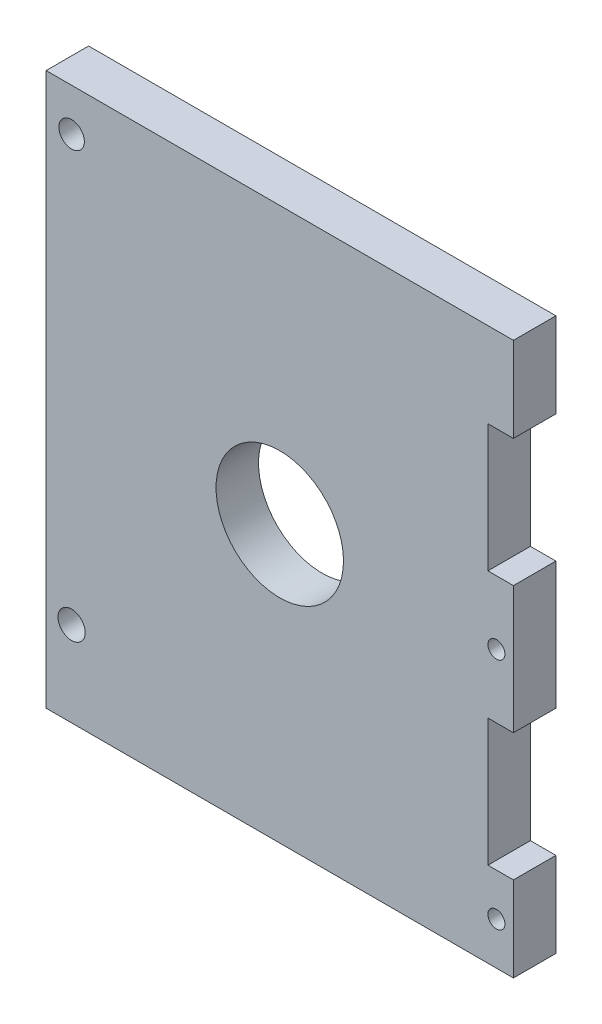
SolidWorks part; units mm, degrees
ref_plane "Front" through (0, 0, 0) normal (0, 0, 1) x (1, 0, 0)
ref_plane "Top" through (0, 0, 0) normal (0, 1, 0) x (1, 0, 0)
ref_plane "Right" through (0, 0, 0) normal (1, 0, 0) x (0, 0, -1)
sketch "草图1" plane through (0, 0, 0) normal (0, 0, 1) x (1, 0, 0)
  line L1 (0, 0) -> (55, 0)
  line L2 (0, 0) -> (0, 65)
  line L3 (0, 65) -> (55, 65)
  line L4 (55, 0) -> (55, 65)
  dimension "D1" = 55
  dimension "D2" = 65
extrude "凸台-拉伸1" add sketch "草图1" along normal blind 5
sketch "草图2" plane through (0, 0, 5) normal (0, 0, 1) x (1, 0, 0)
  line L0 (55, 0) -> (55, 65) construction
  line L1 (55, 55) -> (52, 55)
  line L2 (55, 55) -> (55, 40)
  line L3 (55, 40) -> (52, 40)
  line L4 (52, 55) -> (52, 40)
  line L5 (55, 65) -> (0, 65) construction
  line L7 (55, 25) -> (52, 25)
  line L8 (55, 25) -> (55, 10)
  line L9 (55, 10) -> (52, 10)
  line L10 (52, 25) -> (52, 10)
  dimension "D1" = 15
  dimension "D2" = 10
  dimension "D3" = 3
  dimension "D4" = 15
  dimension "D5" = 3
  dimension "D6" = 15
extrude "切除-拉伸1" cut sketch "草图2" against normal through all
ref_plane "基准面1" through (0, 65, 5) normal (0, -1, 0) x (-1, 0, 0)
sketch "草图4" plane through (0, 0, 5) normal (0, 0, 1) x (1, 0, 0)
  circle A0 centre (27.5, 32.5) radius 7.5
  dimension "D1" = 15
extrude "切除-拉伸2" cut sketch "草图4" against normal through all
sketch "草图5" plane through (0, 0, 5) normal (0, 0, 1) x (1, 0, 0)
  line L0 (0, 65) -> (0, 0) construction
  line L1 (-17.875, 65) -> (17.875, 65) construction
  line L2 (0, 0) -> (55, 0) construction
  circle A0 centre (3, 60) radius 1.5
  circle A1 centre (3, 10) radius 1.6
  dimension "D1" = 3
  dimension "D2" = 5
  dimension "D3" = 10
extrude "切除-拉伸3" cut sketch "草图5" against normal through all
sketch "草图6" plane through (0, 0, 0) normal (0, 0, -1) x (-1, 0, 0)
  line L0 (-55, 25) -> (-55, 40) construction
  circle A0 centre (-53, 32.5) radius 1
  circle A1 centre (-53, 5) radius 1
  dimension "D1" = 2
extrude "切除-拉伸4" cut sketch "草图6" against normal through all
